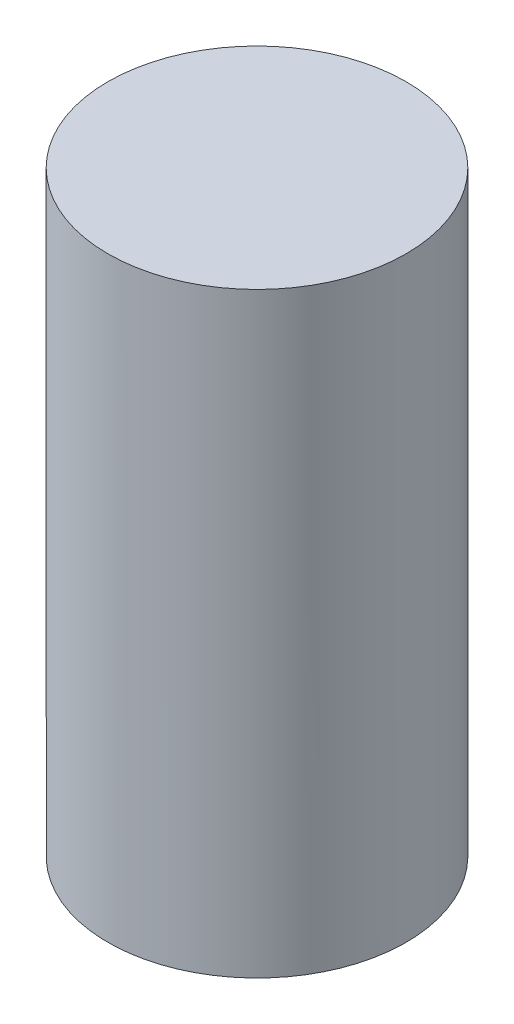
SolidWorks part; units mm, degrees
ref_plane "Front Plane" through (0, 0, 0) normal (0, 0, 1) x (1, 0, 0)
ref_plane "Top Plane" through (0, 0, 0) normal (0, 1, 0) x (1, 0, 0)
ref_plane "Right Plane" through (0, 0, 0) normal (1, 0, 0) x (0, 0, -1)
sketch "Sketch2" plane through (0, 0, 0) normal (0, 1, 0) x (1, 0, 0)
  line L0 (0, 0) -> (0, 5) construction
  line L1 (1.299, 0.75) -> (3.4641, -0.5)
  line L2 (1.299, 0.75) -> (1.299, 3.25)
  line L3 (0, 0) -> (-3.0311, 1.75) construction
  line L4 (-1.299, 0.75) -> (-1.299, 3.25)
  line L5 (-1.299, 0.75) -> (-3.4641, -0.5)
  line L10 (0, -1.5) -> (-2.1651, -2.75)
  line L11 (0, -1.5) -> (2.1651, -2.75)
  circle A0 centre (0, 0) radius 5
  arc A1 (-1.299, 3.25) -> (-3.4641, -0.5) centre (0, 0) ccw
  arc A4 (3.4641, -0.5) -> (1.299, 3.25) centre (0, 0) ccw
  arc A5 (-2.1651, -2.75) -> (2.1651, -2.75) centre (0, 0) ccw
  point P9 (0, 0)
  point P17 (0, 0)
  point P20 (0, 0)
  dimension "D1" = 10
  dimension "D2" = 7
  dimension "D4" = 60
  dimension "D5" = 1.5
  dimension "D3" = 3
extrude "Boss-Extrude1" add sketch "Sketch2" along normal blind 15
sketch "Sketch3" plane through (0, 0, 0) normal (0, -1, 0) x (1, 0, 0)
  line L0 (0, 0) -> (0, 1.5) construction
  line L1 (0, 1.5) -> (0, 3.5) construction
  line L2 (0, 1.5) -> (-2.1651, 2.75) construction
  circle A4 centre (0, 0) radius 5
  circle A5 centre (0, 0) radius 5 construction
  arc A6 (2.1651, 2.75) -> (-2.1651, 2.75) centre (0, 0) ccw construction
  circle A7 centre (0, 2.5) radius 0.75
  circle A8 centre (2.1651, -1.25) radius 0.75
  circle A9 centre (-2.1651, -1.25) radius 0.75
  point P16 (0, 0)
  point P22 (0, 0)
  dimension "D1" = 1.5
  dimension "D2" = 3
extrude "Boss-Extrude2" add sketch "Sketch3" along normal blind 2
sketch "Sketch4" plane through (0, 15, 0) normal (0, 1, 0) x (1, 0, 0)
  circle A0 centre (0, 0) radius 5
  circle A1 centre (0, 0) radius 5 construction
extrude "Boss-Extrude3" add sketch "Sketch4" along normal blind 3
